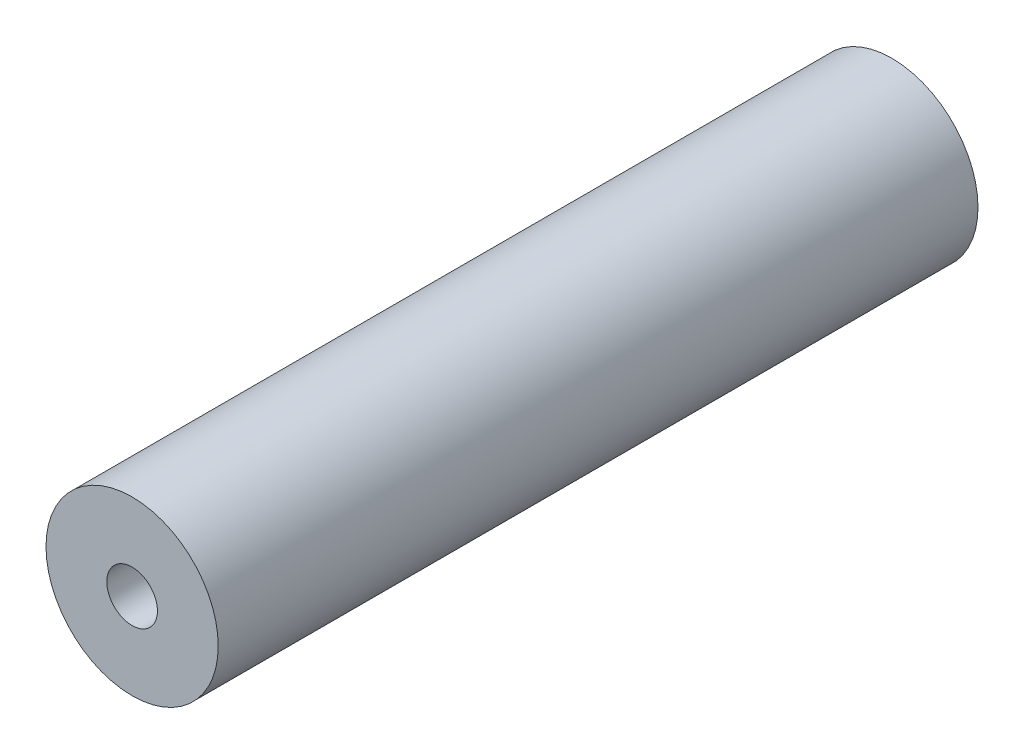
SolidWorks part; units mm, degrees
ref_plane "Front Plane" through (0, 0, 0) normal (0, 0, 1) x (1, 0, 0)
ref_plane "Top Plane" through (0, 0, 0) normal (0, 1, 0) x (1, 0, 0)
ref_plane "Right Plane" through (0, 0, 0) normal (1, 0, 0) x (0, 0, -1)
sketch "Sketch1" plane through (0, 0, 0) normal (0, 0, 1) x (1, 0, 0)
  circle A0 centre (0, 0) radius 17
  dimension "D1" = 34
extrude "Boss-Extrude1" add sketch "Sketch1" along normal blind 150
sketch "Sketch2" plane through (0, 0, 150) normal (0, 0, 1) x (1, 0, 0)
  circle A0 centre (0, 0) radius 5
  dimension "D1" = 10
extrude "Cut-Extrude1" cut sketch "Sketch2" against normal blind 150 contours A0
